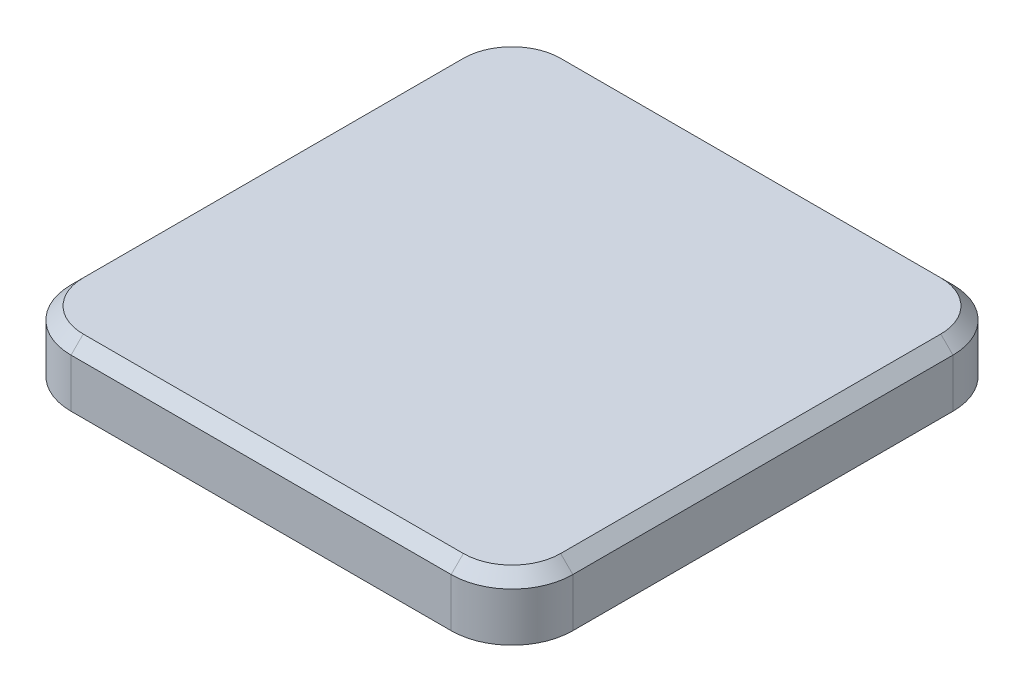
SolidWorks part; units mm, degrees
ref_plane "Plan de face" through (0, 0, 0) normal (0, 0, 1) x (1, 0, 0)
ref_plane "Plan de dessus" through (0, 0, 0) normal (0, 1, 0) x (1, 0, 0)
ref_plane "Plan de droite" through (0, 0, 0) normal (1, 0, 0) x (0, 0, -1)
sketch "Esquisse1" plane through (0, 0, 0) normal (0, 1, 0) x (1, 0, 0)
  line L0 (-8.25, 8.25) -> (8.25, -8.25) construction
  line L1 (8.25, -8.25) -> (-8.25, -8.25)
  line L2 (8.25, -8.25) -> (8.25, 8.25)
  line L3 (8.25, 8.25) -> (-8.25, 8.25)
  line L4 (-8.25, -8.25) -> (-8.25, 8.25)
  point P4 (0, 0)
  dimension "D1" = 16.5
extrude "Boss.-Extru.1" add sketch "Esquisse1" along normal blind 2
sketch "Esquisse2" plane through (0, 0, 0) normal (0, -1, 0) x (1, 0, 0)
  line L0 (-2.35, 0) -> (-3.35, 0)
  line L1 (-3.35, 0) -> (-3.35, 0.5)
  line L2 (-3.35, 0.5) -> (-3.45, 0.5)
  line L3 (-3.45, 0.5) -> (-3.45, 1.45)
  line L4 (-3.45, 1.45) -> (-2.25, 1.45)
  line L5 (-2.25, 1.45) -> (-2.25, 0.5)
  line L6 (-2.25, 0.5) -> (-2.35, 0.5)
  line L7 (-2.35, 0.5) -> (-2.35, 0)
  line L8 (0, 0) -> (-5.7233, 0) construction
  line L9 (0, 0) -> (0, 3.8974) construction
  line L11 (-3.35, 0) -> (-2.35, 0)
  line L12 (-3.35, 0) -> (-3.35, -0.4759)
  line L13 (-3.35, -0.4759) -> (-2.35, -0.4759)
  line L14 (-2.35, 0) -> (-2.35, -0.4759)
  point P10 (-2.85, 1.45)
  point P11 (-2.85, 0)
  dimension "D1" = 2.9
  dimension "D2" = 6.9
  dimension "D3" = 1.2
  dimension "D4" = 1
  dimension "D5" = 0.5
extrude "Boss.-Extru.2" add sketch "Esquisse2" along normal blind 3 draft 2 contours L14 L0 L12 L13 | L7 L6 L5 L4 L3 L2 L1 L0
mirror "Symétrie1" about plane through (0, 0, 0) normal (0, 0, 1) of "Boss.-Extru.2"
mirror "Symétrie2" about plane through (0, 0, 0) normal (1, 0, 0) of "Symétrie1", "Boss.-Extru.2"
fillet "Congé1" radius 2 4 edges at (8.25, 1, -8.25) (8.25, 1, 8.25) (-8.25, 1, 8.25) (-8.25, 1, -8.25)
chamfer "Chanfrein1" distance 0.4 angle 45 8 edges at (0, 2, 8.25) (7.6642, 2, 7.6642) (-7.6642, 2, 7.6642) (8.25, 2, 0) (-8.25, 2, 0) (7.6642, 2, -7.6642) (-7.6642, 2, -7.6642) (0, 2, -8.25)
sketch "Esquisse3" plane through (0, 0, 0) normal (0, -1, 0) x (1, 0, 0)
  line L1 (2.5, -2.6) -> (-2.5, -2.6) construction
  line L2 (2.5, -2.6) -> (2.5, -5.6) construction
  line L3 (2.5, -5.6) -> (-2.5, -5.6) construction
  line L4 (-2.5, -2.6) -> (-2.5, -5.6) construction
  text T0 "G" font "Arial Rounded MT Bold" height 3.5
  point P4 (0, -2.6)
  dimension "D1" = 3
  dimension "D2" = 5
  dimension "D3" = 2.6
extrude "Enlèv. mat.-Extru.1" cut sketch "Esquisse3" against normal blind 1.6
